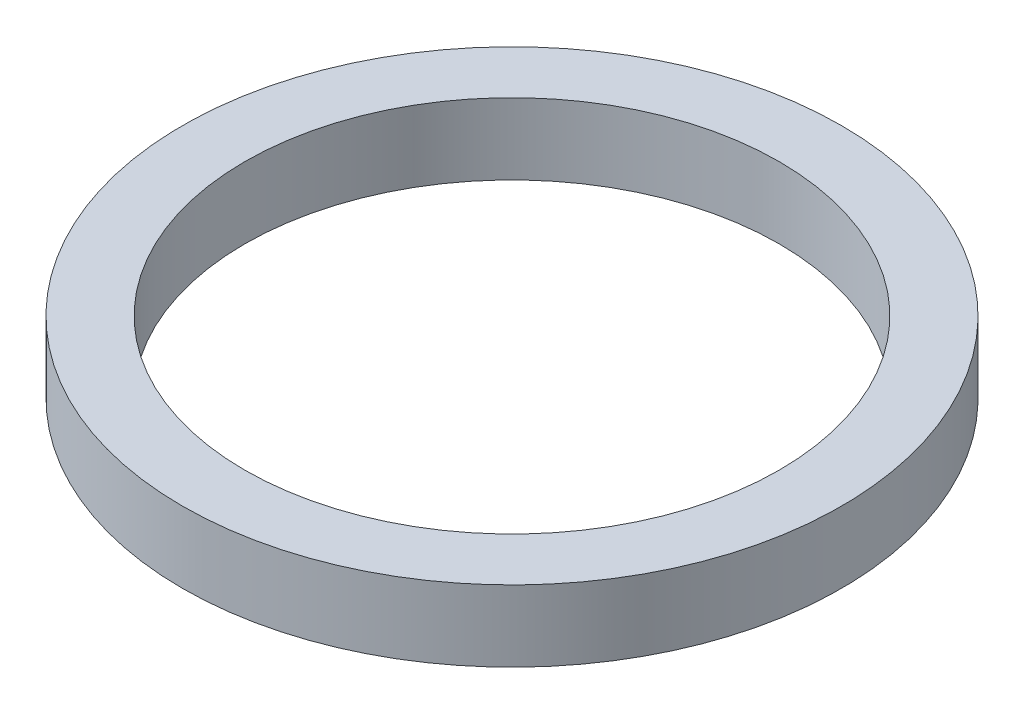
SolidWorks part; units mm, degrees
ref_plane "Ön Düzlem" through (0, 0, 0) normal (0, 0, 1) x (1, 0, 0)
ref_plane "Üst Düzlem" through (0, 0, 0) normal (0, 1, 0) x (1, 0, 0)
ref_plane "Sağ Düzlem" through (0, 0, 0) normal (1, 0, 0) x (0, 0, -1)
sketch "Sketch1" plane through (0, 0, 0) normal (0, 1, 0) x (1, 0, 0)
  circle A0 centre (0, 0) radius 15
  circle A1 centre (0, 0) radius 18.5
  dimension "D1" = 37
  dimension "D2" = 30
extrude "Boss-Extrude1" add sketch "Sketch1" along normal blind 4
